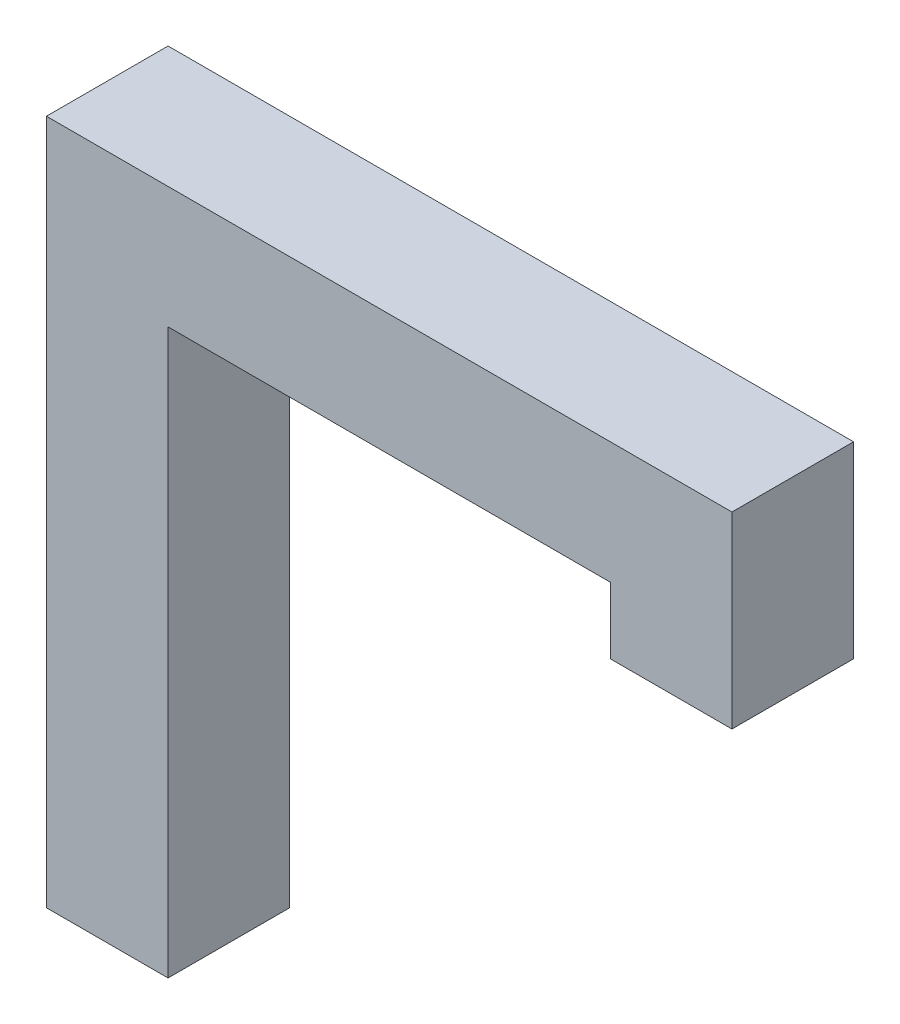
SolidWorks part; units mm, degrees
material "ﾁｰｸ材"
ref_plane "正面" through (0, 0, 0) normal (0, 0, 1) x (1, 0, 0)
ref_plane "平面" through (0, 0, 0) normal (0, 1, 0) x (1, 0, 0)
ref_plane "右側面" through (0, 0, 0) normal (1, 0, 0) x (0, 0, -1)
sketch "ｽｹｯﾁ1" plane through (0, 0, 0) normal (0, 0, 1) x (1, 0, 0)
  line L0 (0, 0) -> (-5.5, 0)
  line L1 (-5.5, 0) -> (-5.5, 31)
  line L2 (-5.5, 31) -> (25.5, 31)
  line L3 (25.5, 31) -> (25.5, 22.5)
  line L4 (25.5, 22.5) -> (20, 22.5)
  line L5 (20, 22.5) -> (20, 25.5)
  line L6 (20, 25.5) -> (0, 25.5)
  line L7 (0, 25.5) -> (0, 0)
  dimension "D1" = 5.5
  dimension "D2" = 25.5
  dimension "D3" = 5.5
  dimension "D4" = 20
  dimension "D5" = 3
  dimension "D6" = 5.5
extrude "ﾎﾞｽ - 押し出し1" add sketch "ｽｹｯﾁ1" along normal blind 5.5
